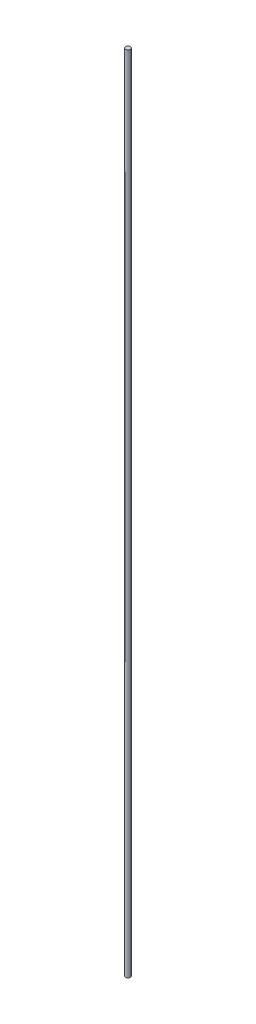
SolidWorks part; units mm, degrees
ref_plane "Front Plane" through (0, 0, 0) normal (0, 0, 1) x (1, 0, 0)
ref_plane "Top Plane" through (0, 0, 0) normal (0, 1, 0) x (1, 0, 0)
ref_plane "Right Plane" through (0, 0, 0) normal (1, 0, 0) x (0, 0, -1)
sketch "Sketch1" plane through (0, 0, 0) normal (0, 0, 1) x (1, 0, 0)
  line L0 (0, 0) -> (0, 2095.246)
  dimension "Length from Tank Model" = 2095.246
sweep "Sweep1" add path "Sketch1" circular profile diameter 12.7 parameters "D3"=12.7
equation "\"rebar diameter\"= .5"
equation "\"D3@Sweep1\"=\"rebar diameter\""
